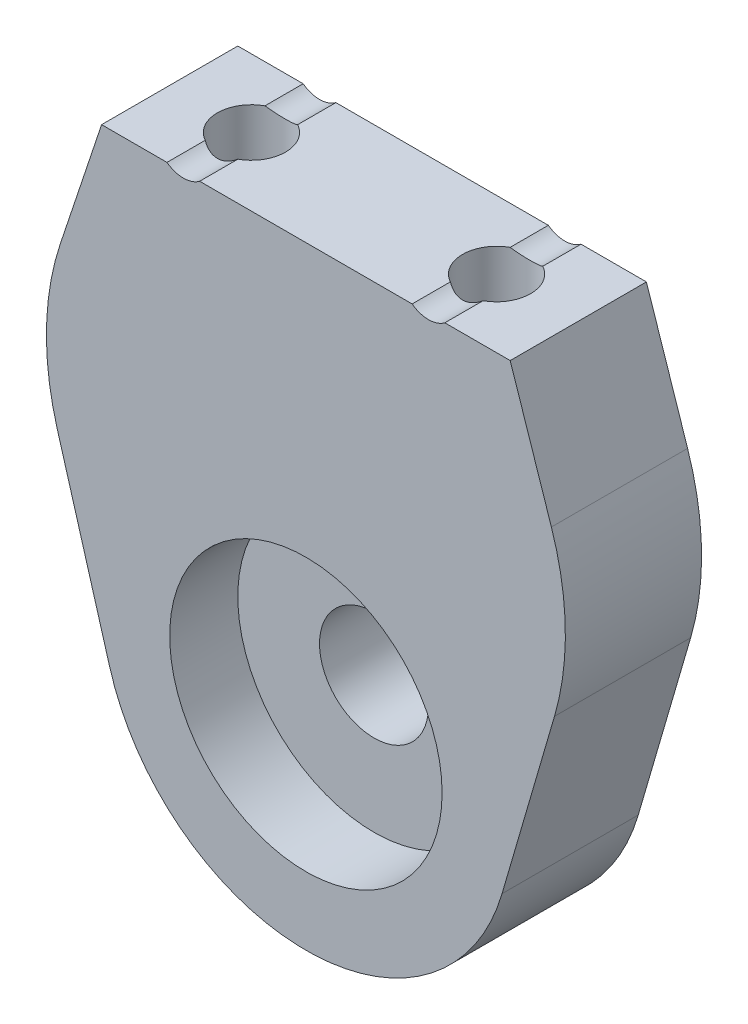
SolidWorks part; units mm, degrees
material "A2017"
ref_plane "正面" through (0, 0, 0) normal (0, 0, 1) x (1, 0, 0)
ref_plane "平面" through (0, 0, 0) normal (0, 1, 0) x (1, 0, 0)
ref_plane "右側面" through (0, 0, 0) normal (1, 0, 0) x (0, 0, -1)
sketch "ｽｹｯﾁ1" plane through (0, 0, 0) normal (0, 0, 1) x (1, 0, 0)
  circle A0 centre (0, 0) radius 7.5
  circle A1 centre (0, 0) radius 2
  dimension "D1" = 4
  dimension "D2" = 15
extrude "ﾎﾞｽ - 押し出し1" add sketch "ｽｹｯﾁ1" along normal blind 5
sketch "ｽｹｯﾁ2" plane through (0, 0, 5) normal (0, 0, 1) x (1, 0, 0)
  line L0 (0, 0) -> (0, 15) construction
  line L1 (-7.5, 0) -> (-7.5, 15)
  line L2 (-7.5, 15) -> (7.5, 15)
  line L3 (7.5, 15) -> (7.5, 0)
  circle A0 centre (0, 0) radius 7.5 construction
  arc A1 (-7.5, 0) -> (7.5, 0) centre (0, 0) cw
  dimension "D1" = 15
extrude "ﾎﾞｽ - 押し出し2" add sketch "ｽｹｯﾁ2" against normal up to surface (5 mm away) up to face at (7.5, 0, 0)
sketch "ｽｹｯﾁ3" plane through (0, 15, 0) normal (0, 1, 0) x (1, 0, 0)
  line L0 (-7.5, -2.5) -> (7.5, -2.5) construction
  line L3 (-7.5, 0) -> (-7.5, -5) construction
  line L4 (7.5, 0) -> (7.5, -5) construction
  line L5 (0, 0) -> (0, -5) construction
  line L6 (-7.5, 0) -> (7.5, 0) construction
  line L7 (7.5, -5) -> (-7.5, -5) construction
  circle A0 centre (-4.5, -2.5) radius 1
  circle A1 centre (4.5, -2.5) radius 1
  dimension "D1" = 3
  dimension "D2" = 2
extrude "ｶｯﾄ - 押し出し1" cut sketch "ｽｹｯﾁ3" against normal blind 5
sketch "ｽｹｯﾁ4" plane through (0, 0, 5) normal (0, 0, 1) x (1, 0, 0)
  line L0 (0, 0) -> (0, 15) construction
  line L1 (7.5, 15) -> (-7.5, 15) construction
  line L2 (0, 7.5) -> (-10, 7.5) construction
  line L3 (-10, 7.5) -> (-7.5, 15) construction
  line L4 (-10, 7.5) -> (-7.2, -2.1) construction
  line L5 (-7.5, 15) -> (-10, 7.5)
  line L6 (-10, 7.5) -> (-7.2, -2.1)
  line L7 (-7.5, 0) -> (-7.5, 15)
  line L8 (10, 7.5) -> (7.2, -2.1) construction
  line L9 (10, 7.5) -> (7.5, 15) construction
  line L10 (7.5, 0) -> (7.5, 15)
  line L11 (10, 7.5) -> (7.2, -2.1)
  line L12 (7.5, 15) -> (10, 7.5)
  arc A0 (-7.5, 0) -> (7.5, 0) centre (0, 0) ccw construction
  arc A1 (-7.2, -2.1) -> (-7.5, 0) centre (0, 0) cw
  arc A2 (7.2, -2.1) -> (7.5, 0) centre (0, 0) ccw
  dimension "D1" = 10
extrude "ﾎﾞｽ - 押し出し3" add sketch "ｽｹｯﾁ4" against normal up to surface (5 mm away) up to face at (0, 5.625, 0)
fillet "ﾌｨﾚｯﾄ1" radius 10 2 edges at (10, 7.5, 2.5) (-10, 7.5, 2.5)
sketch "ｽｹｯﾁ5" plane through (0, 0, 5) normal (0, 0, 1) x (1, 0, 0)
  line L0 (0, 0) -> (0, 12) construction
  line L1 (0, 12) -> (-8.1875, 12) construction
  line L2 (-9.1253, 4.5012) -> (-7.2, -2.1) construction
  line L3 (-8.1875, 15) -> (8.1875, 15)
  line L4 (9.0122, 10.4635) -> (7.5, 15) construction
  line L5 (7.5, 15) -> (-7.5, 15) construction
  line L6 (-7.5, 15) -> (-9.0122, 10.4635) construction
  line L7 (9.0122, 10.4635) -> (7.5, 15)
  line L8 (7.5, 15) -> (-7.5, 15)
  line L9 (-7.5, 15) -> (-9.0122, 10.4635)
  arc A0 (-8.1875, 15) -> (-6.4921, 14.475) centre (-8.1875, 12) ccw
  arc A1 (8.1875, 15) -> (6.4921, 14.475) centre (8.1875, 12) cw
  arc A2 (9.1253, 4.5012) -> (9.0122, 10.4635) centre (-0.4747, 7.3012) ccw construction
  arc A3 (-9.0122, 10.4635) -> (-9.1253, 4.5012) centre (0.4747, 7.3012) ccw construction
  arc A4 (6.4921, 14.475) -> (9.0122, 10.4635) centre (-0.4747, 7.3012) ccw
  arc A5 (-9.0122, 10.4635) -> (-6.4921, 14.475) centre (0.4747, 7.3012) ccw
  dimension "D2" = 6
  dimension "D1" = 12
extrude "ｶｯﾄ - 押し出し2" [suppressed] cut sketch "ｽｹｯﾁ5" against normal through all
sketch "ｽｹｯﾁ6" [suppressed] plane through (0, 0, 5) normal (0, 0, 1) x (1, 0, 0)
  arc A0 (9.8123, 12.4863) -> (6.852, 15) centre (6.852, 12) ccw construction
  arc A1 (-6.852, 15) -> (-9.8123, 12.4863) centre (-6.852, 12) ccw construction
  circle A2 centre (6.852, 12) radius 3
  circle A3 centre (-6.852, 12) radius 3
extrude "ﾎﾞｽ - 押し出し4" [suppressed] add sketch "ｽｹｯﾁ6" against normal up to surface (5 mm away)
sketch "ｽｹｯﾁ7" [suppressed] plane through (0, 0, 5) normal (0, 0, 1) x (1, 0, 0)
  circle A0 centre (6.852, 12) radius 1.5
  circle A1 centre (-6.852, 12) radius 1.5
  dimension "D1" = 3
  dimension "D2" = 3
extrude "ｶｯﾄ - 押し出し3" [suppressed] cut sketch "ｽｹｯﾁ7" against normal through all
sketch "ｽｹｯﾁ8" [suppressed] plane through (0, 0, 5) normal (0, 0, 1) x (1, 0, 0)
  line L0 (-6.852, 15) -> (-9.852, 15)
  line L1 (-9.852, 15) -> (-9.852, 11.7185)
  line L2 (-9.852, 11.7185) -> (-9.7997, 11.4419)
  line L3 (0, 0) -> (0, 15) construction
  line L4 (-6.852, 15) -> (6.852, 15) construction
  line L5 (9.852, 11.7185) -> (9.7997, 11.4419)
  line L6 (9.852, 15) -> (9.852, 11.7185)
  line L7 (6.852, 15) -> (9.852, 15)
  arc A0 (-7.3691, -1.3953) -> (7.3691, -1.3953) centre (0, 0) ccw construction
  arc A1 (-6.852, 15) -> (-9.7269, 11.1426) centre (-6.852, 12) ccw construction
  arc A2 (-6.852, 15) -> (-9.7997, 11.4419) centre (-6.852, 12) ccw
  arc A3 (6.852, 15) -> (9.7997, 11.4419) centre (6.852, 12) cw
extrude "ﾎﾞｽ - 押し出し5" [suppressed] add sketch "ｽｹｯﾁ8" against normal up to surface (5 mm away)
sketch "ｽｹｯﾁ10" [suppressed] plane through (0, 0, 0) normal (0, 0, -1) x (-1, 0, 0)
  line L0 (0, 15) -> (0, 0) construction
  line L1 (9.852, 15) -> (-9.852, 15) construction
sketch "ｽｹｯﾁ11" plane through (0, 0, 5) normal (0, 0, 1) x (1, 0, 0)
  circle A0 centre (0, 0) radius 5
  dimension "D1" = 10
extrude "ｶｯﾄ - 押し出し4" cut sketch "ｽｹｯﾁ11" against normal blind 2.5
sketch "ｽｹｯﾁ12" plane through (0, 0, 0) normal (0, 0, -1) x (-1, 0, 0)
  line L0 (-4.5, 10) -> (-4.5, 15.8) construction
  line L1 (-3.5, 10) -> (-5.5, 10) construction
  line L2 (7.5, 15) -> (-7.5, 15) construction
  line L3 (0, 0) -> (0, 15) construction
  circle A0 centre (-4.5, 15.8) radius 1
  circle A1 centre (4.5, 15.8) radius 1
  dimension "D1" = 2
  dimension "D2" = 0.8
extrude "ｶｯﾄ - 押し出し5" cut sketch "ｽｹｯﾁ12" against normal through all
hole_wizard "M3 ねじ穴1" positions "ｽｹｯﾁ13" profile "ｽｹｯﾁ14" tap size "M3" standard "JIS"
sketch "ｽｹｯﾁ13" plane through (0, 15, 0) normal (0, 1, 0) x (1, 0, 0)
  point P0 (-4.5, -2.5)
  point P3 (4.5, -2.5)
sketch "ｽｹｯﾁ14" plane through (-4.5, 15, 2.5) normal (1, 0, 0) x (0, 0, 1)
  line L0 (0, 0) -> (0, 9.2511)
  line L1 (0, 9.2511) -> (1.25, 8.5)
  line L2 (1.25, 8.5) -> (1.25, 0)
  line L5 (1.25, 0) -> (0, 0)
  line L10 (0, 9.2511) -> (-1.25, 8.5) construction
  line L11 (0, -6.35) -> (0, 107.95) construction
  dimension "ねじ下穴ﾄﾞﾘﾙ直径" = 2.5
  dimension "ねじ下穴ﾄﾞﾘﾙの深さ" = 8.5
  dimension "ﾄﾞﾘﾙ角度" = 118
cosmetic thread "穴のねじ山1" parameters "D1"=6, "D2"=3
cosmetic thread "穴のねじ山2" parameters "D1"=6, "D2"=3
